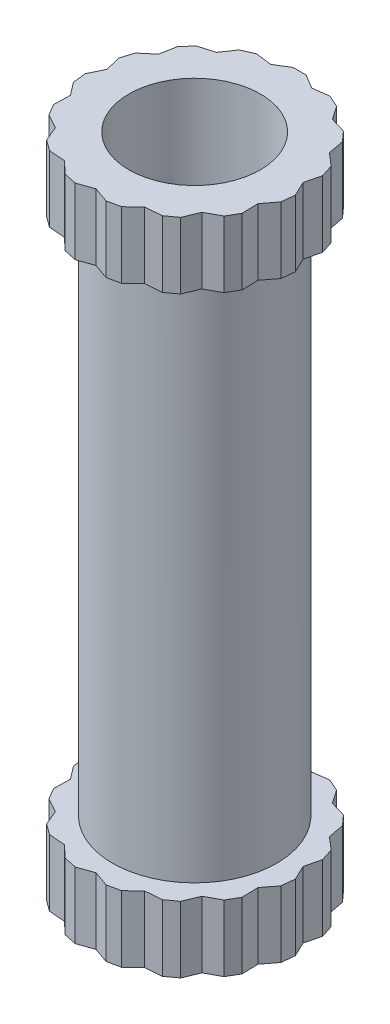
SolidWorks part; units mm, degrees
ref_plane "Front Plane" through (0, 0, 0) normal (0, 0, 1) x (1, 0, 0)
ref_plane "Top Plane" through (0, 0, 0) normal (0, 1, 0) x (1, 0, 0)
ref_plane "Right Plane" through (0, 0, 0) normal (1, 0, 0) x (0, 0, -1)
sketch "Sketch1" plane through (0, 0, 0) normal (0, 1, 0) x (1, 0, 0)
  circle A0 centre (0, 0) radius 1.25
  circle A1 centre (0, 0) radius 1
  dimension "D1" = 2.5
  dimension "D2" = 2
extrude "Boss-Extrude1" add sketch "Sketch1" along normal blind 4
sketch "Sketch2" plane through (0, 4, 0) normal (0, 1, 0) x (1, 0, 0)
  line L0 (0, 0) -> (0, 1.6) construction
  line L1 (0, 0) -> (-0.3327, 1.565) construction
  line L2 (-0.3119, 1.4672) -> (-0.1, 1.5969)
  line L3 (-0.1, 1.5969) -> (0.1, 1.5969)
  line L4 (0.3119, 1.4672) -> (0.5582, 1.4995)
  line L5 (0.3119, 1.4672) -> (0.1, 1.5969)
  line L6 (0.5582, 1.4995) -> (0.7409, 1.4181)
  line L7 (0.8817, 1.2135) -> (0.7409, 1.4181)
  line L8 (0.8817, 1.2135) -> (1.1198, 1.1428)
  line L9 (1.1198, 1.1428) -> (1.2536, 0.9942)
  line L10 (1.299, 0.75) -> (1.2536, 0.9942)
  line L11 (1.299, 0.75) -> (1.4878, 0.5886)
  line L12 (1.4878, 0.5886) -> (1.5496, 0.3984)
  line L13 (1.4918, 0.1568) -> (1.5496, 0.3984)
  line L14 (1.4918, 0.1568) -> (1.5986, -0.0675)
  line L15 (1.5986, -0.0675) -> (1.5777, -0.2664)
  line L16 (1.4266, -0.4635) -> (1.5777, -0.2664)
  line L17 (1.4266, -0.4635) -> (1.4329, -0.7118)
  line L18 (1.4329, -0.7118) -> (1.3329, -0.885)
  line L19 (1.1147, -1.0037) -> (1.3329, -0.885)
  line L20 (1.1147, -1.0037) -> (1.0195, -1.2331)
  line L21 (1.0195, -1.2331) -> (0.8577, -1.3507)
  line L22 (0.6101, -1.3703) -> (0.8577, -1.3507)
  line L23 (0.6101, -1.3703) -> (0.4298, -1.5412)
  line L24 (0.4298, -1.5412) -> (0.2342, -1.5828)
  line L25 (0, -1.5) -> (0.2342, -1.5828)
  line L26 (0, -1.5) -> (-0.2342, -1.5828)
  line L27 (-0.2342, -1.5828) -> (-0.4298, -1.5412)
  line L28 (-0.6101, -1.3703) -> (-0.4298, -1.5412)
  line L29 (-0.6101, -1.3703) -> (-0.8577, -1.3507)
  line L30 (-0.8577, -1.3507) -> (-1.0195, -1.2331)
  line L31 (-1.1147, -1.0037) -> (-1.0195, -1.2331)
  line L32 (-1.1147, -1.0037) -> (-1.3329, -0.885)
  line L33 (-1.3329, -0.885) -> (-1.4329, -0.7118)
  line L34 (-1.4266, -0.4635) -> (-1.4329, -0.7118)
  line L35 (-1.4266, -0.4635) -> (-1.5777, -0.2664)
  line L36 (-1.5777, -0.2664) -> (-1.5986, -0.0675)
  line L37 (-1.4918, 0.1568) -> (-1.5986, -0.0675)
  line L38 (-1.4918, 0.1568) -> (-1.5496, 0.3984)
  line L39 (-1.5496, 0.3984) -> (-1.4878, 0.5886)
  line L40 (-1.299, 0.75) -> (-1.4878, 0.5886)
  line L41 (-1.299, 0.75) -> (-1.2536, 0.9942)
  line L42 (-1.2536, 0.9942) -> (-1.1198, 1.1428)
  line L43 (-0.8817, 1.2135) -> (-1.1198, 1.1428)
  line L44 (-0.8817, 1.2135) -> (-0.7409, 1.4181)
  line L45 (-0.7409, 1.4181) -> (-0.5582, 1.4995)
  line L46 (-0.3119, 1.4672) -> (-0.5582, 1.4995)
  circle A22 centre (0, 0) radius 1 construction
  circle A23 centre (0, 0) radius 1
  circle A24 centre (0, 0) radius 1.6
  circle A25 centre (0, 0) radius 1.5
  point P69 (0, 0)
  dimension "D1" = 3.2
  dimension "D2" = 3
  dimension "D3" = 12
  dimension "D4" = 0.2
extrude "Boss-Extrude2" add sketch "Sketch2" along normal blind 1.01
mirror "Mirror1" about plane through (0, 0, 0) normal (0, 1, 0) of "Boss-Extrude1", "Boss-Extrude2"
